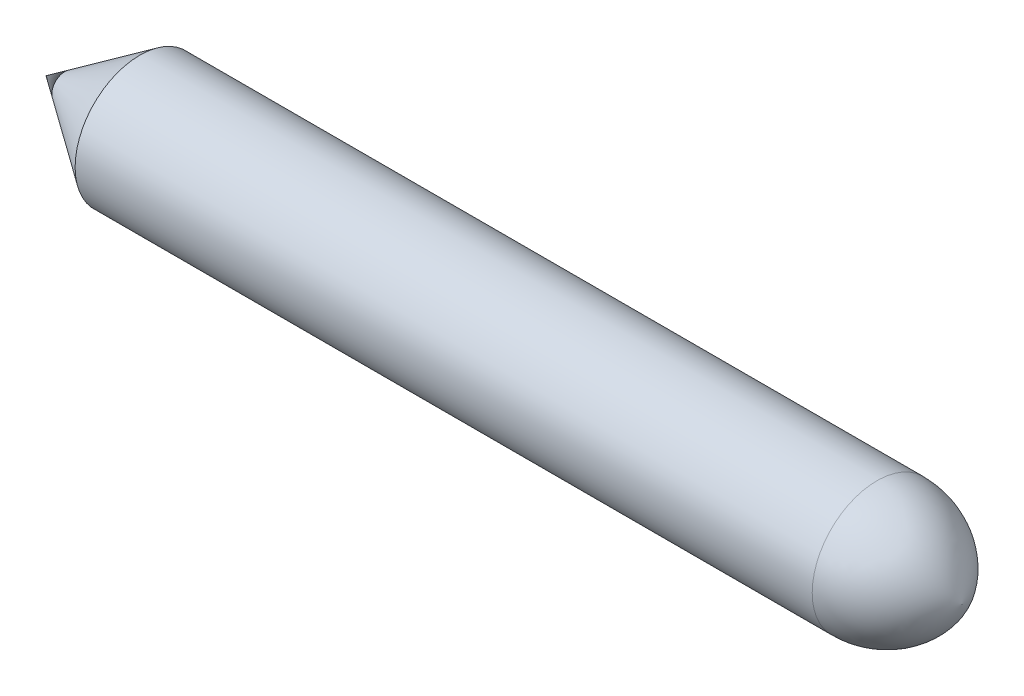
SolidWorks part; units mm, degrees
ref_plane "Alzado" through (0, 0, 0) normal (0, 0, 1) x (1, 0, 0)
ref_plane "Planta" through (0, 0, 0) normal (0, 1, 0) x (1, 0, 0)
ref_plane "Vista lateral" through (0, 0, 0) normal (1, 0, 0) x (0, 0, -1)
sketch "Croquis1" plane through (0, 0, 0) normal (0, 1, 0) x (1, 0, 0)
  line L0 (0, 0) -> (74.7452, 0)
  line L1 (0, 0) -> (7.6608, 5.2844)
  line L2 (7.6608, 5.2844) -> (67.8267, 5.2844)
  arc A0 (67.8267, 5.2844) -> (74.7452, 0) centre (67.8267, -1.8868) cw
revolve "Revolución2" add sketch "Croquis1" angle 360 about L0
